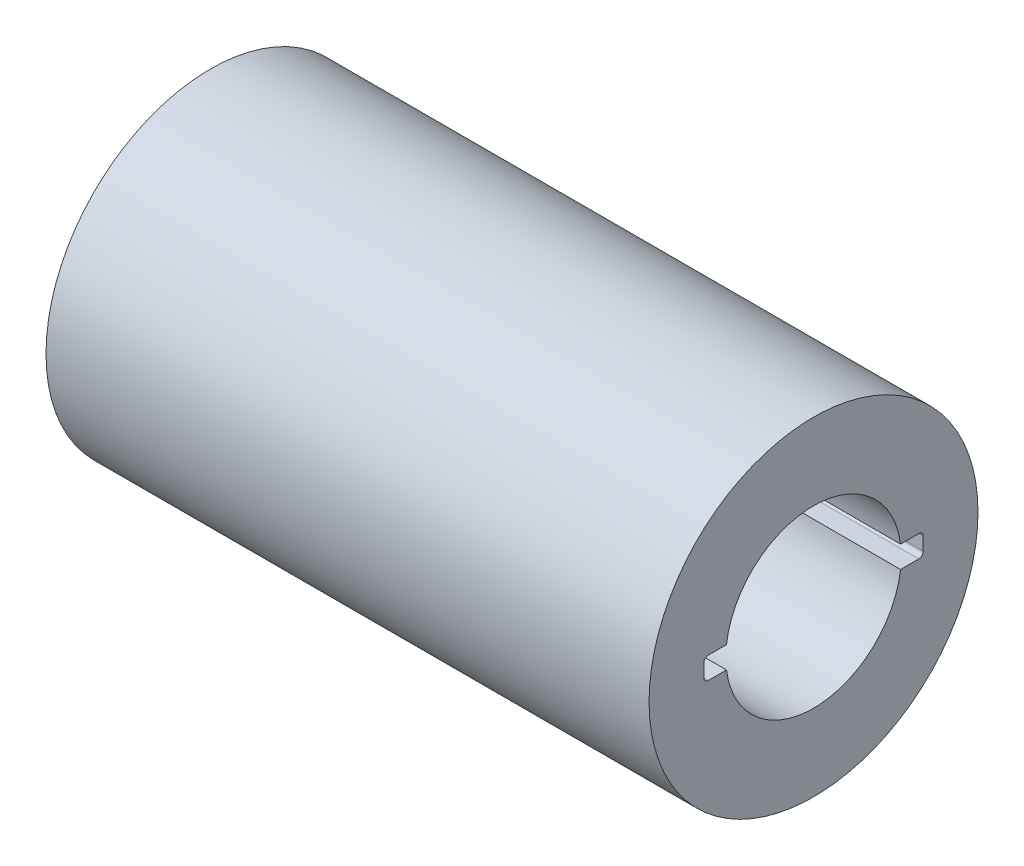
SolidWorks part; units mm, degrees
ref_plane "Front Plane" through (0, 0, 0) normal (0, 0, 1) x (1, 0, 0)
ref_plane "Top Plane" through (0, 0, 0) normal (0, 1, 0) x (1, 0, 0)
ref_plane "Right Plane" through (0, 0, 0) normal (1, 0, 0) x (0, 0, -1)
sketch "Sketch1" plane through (0, 0, 0) normal (1, 0, 0) x (0, 0, -1)
  circle A0 centre (0, 0) radius 7.5
  circle A1 centre (0, 0) radius 4
  dimension "D1" = 15
  dimension "D2" = 8
extrude "ScrewSide" add sketch "Sketch1" along normal blind 10
sketch "Sketch4" plane through (0, 0, 0) normal (-1, 0, 0) x (0, 0, 1)
  line L0 (-1.5, -2) -> (1.5, -2)
  line L1 (0, 2.5) -> (0, 0) construction
  circle A1 centre (0, 0) radius 7.5
  arc A2 (1.5, -2) -> (-1.5, -2) centre (0, 0) ccw
  arc A3 (-1.5, -2) -> (1.5, -2) centre (0, 0) ccw construction
  point P6 (0, 2.5)
  dimension "D1" = 5
  dimension "D2" = 4.5
extrude "MotorSide" add sketch "Sketch4" along normal blind 17.5
sketch "Sketch6" plane through (-17.5, 0, 0) normal (-1, 0, 0) x (0, 0, 1)
  line L0 (0, 0) -> (2.5, 0) construction
  line L1 (-3.5, -0.5) -> (3.5, -0.5)
  line L2 (-3.5, -0.5) -> (-3.5, 0.5)
  line L3 (-3.5, 0.5) -> (3.5, 0.5)
  line L4 (3.5, -0.5) -> (3.5, 0.5)
  line L5 (-3.5, -0.5) -> (3.5, 0.5) construction
  line L6 (-3.5, 0.5) -> (3.5, -0.5) construction
  point P0 (0, 0)
  point P6 (2.5, 0)
  dimension "D1" = 1
  dimension "D2" = 1
extrude "Escape Holes" cut sketch "Sketch6" against normal through all
sketch "Sketch7" plane through (10, 0, 0) normal (1, 0, 0) x (0, 0, -1)
  line L0 (0, 0) -> (4, 0) construction
  line L1 (-5, -0.5) -> (5, -0.5)
  line L2 (-5, -0.5) -> (-5, 0.5)
  line L3 (-5, 0.5) -> (5, 0.5)
  line L4 (5, -0.5) -> (5, 0.5)
  line L5 (-5, -0.5) -> (5, 0.5) construction
  line L6 (-5, 0.5) -> (5, -0.5) construction
  point P0 (0, 0)
  dimension "D1" = 1
  dimension "D2" = 1
extrude "Escape Holes 2" cut sketch "Sketch7" against normal up to surface (10 mm away) up to face at (0, -0.2174, 0)
fillet "Fillet1" radius 0.2 8 edges at (-8.75, -0.5, -3.5) (-8.75, 0.5, -3.5) (-8.75, -0.5, 3.5) (-8.75, 0.5, 3.5) (5, -0.5, -5) (5, 0.5, -5) (5, -0.5, 5) (5, 0.5, 5)
sketch "Sketch8" plane through (0, -2, 0) normal (0, 1, 0) x (1, 0, 0)
  line L0 (0, 0) -> (-17.5, 0) construction
  line L1 (-17.5, 7.5) -> (-17.5, -7.5) construction
  circle A0 centre (-5, 0) radius 1.45
  dimension "D2" = 2.9
  dimension "D1" = 5
extrude "Cut-Extrude3" cut sketch "Sketch8" against normal through all contours A0 L0 | L0 A0
